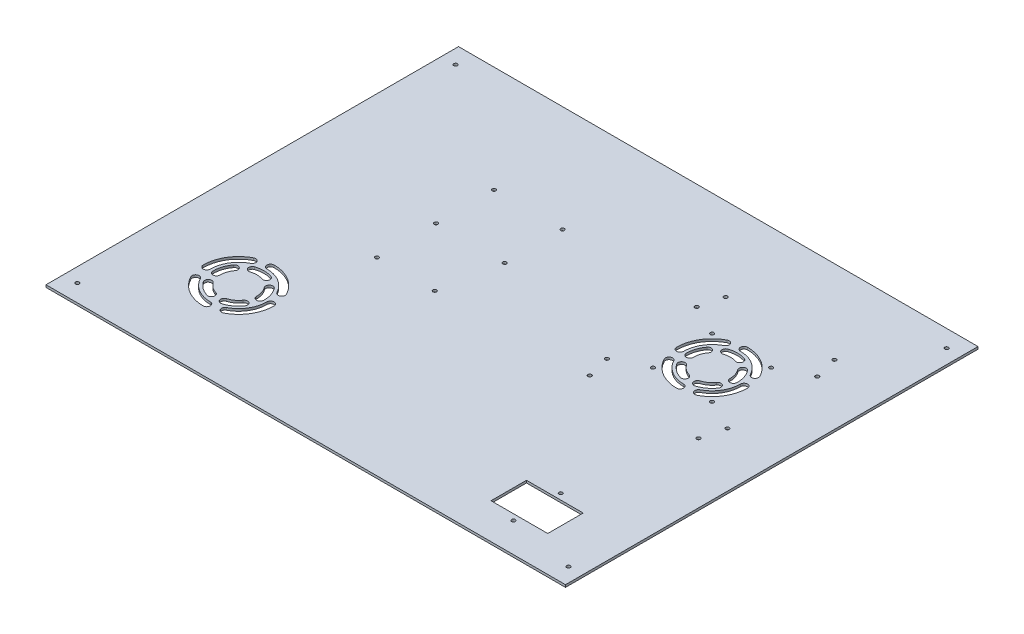
SolidWorks part; units mm, degrees
ref_plane "Alzado" through (0, 0, 0) normal (0, 0, 1) x (1, 0, 0)
ref_plane "Planta" through (0, 0, 0) normal (0, 1, 0) x (1, 0, 0)
ref_plane "Vista lateral" through (0, 0, 0) normal (1, 0, 0) x (0, 0, -1)
sketch "Croquis1" plane through (0, 0, 0) normal (0, 1, 0) x (1, 0, 0)
  line L1 (0, 0) -> (440.5, 0)
  line L2 (0, 0) -> (0, 320)
  line L3 (0, 320) -> (440.5, 320)
  line L4 (440.5, 0) -> (440.5, 320)
  dimension "D1" = 320
  dimension "D2" = 440.5
extrude "Saliente-Extruir1" add sketch "Croquis1" along normal blind 2
sketch "Croquis2" plane through (0, 2, 0) normal (0, 1, 0) x (1, 0, 0)
  line L0 (440.5, 320) -> (0, 320) construction
  line L1 (0, 320) -> (0, 0) construction
  line L2 (220.25, 320) -> (220.25, 0) construction
  line L3 (0, 0) -> (440.5, 0) construction
  line L4 (0, 160) -> (440.5, 160) construction
  line L5 (440.5, 0) -> (440.5, 320) construction
  circle A0 centre (12.5, 305) radius 1.55
  circle A1 centre (428, 305) radius 1.55
  circle A2 centre (428, 15) radius 1.55
  circle A3 centre (12.5, 15) radius 1.55
  dimension "D1" = 3.1
  dimension "D2" = 15
  dimension "D3" = 12.5
extrude "Cortar-Extruir1" cut sketch "Croquis2" against normal up to surface (2 mm away) up to face at (220.25, 0, -160)
sketch "Croquis3" plane through (0, 2, 0) normal (0, 1, 0) x (1, 0, 0)
  line L0 (440, 319.5) -> (0.5, 319.5)
  line L1 (0.5, 319.5) -> (0.5, 0.5)
  line L2 (0.5, 0.5) -> (440, 0.5)
  line L3 (440, 0.5) -> (440, 319.5)
  line L4 (0, 320) -> (0, 0)
  line L5 (0, 0) -> (440.5, 0)
  line L6 (440.5, 0) -> (440.5, 320)
  line L7 (440.5, 320) -> (0, 320)
  line L8 (0, 320) -> (0, 0)
  line L9 (0, 0) -> (440.5, 0)
  line L10 (440.5, 0) -> (440.5, 320)
  line L11 (440.5, 320) -> (0, 320)
  dimension "D1" = 0
  dimension "D2" = 0.5
extrude "Cortar-Extruir2" cut sketch "Croquis3" against normal up to surface (2 mm away) up to face at (12.5, 0, -16.55)
sketch "Croquis4" plane through (0, 2, 0) normal (0, 1, 0) x (1, 0, 0)
  line L0 (0.5, 0.5) -> (440, 0.5) construction
  line L1 (0.5, 319.5) -> (0.5, 0.5) construction
  line L2 (440, 0.5) -> (440, 319.5) construction
  line L4 (440, 319.5) -> (0.5, 319.5) construction
  line L13 (394, 259.5) -> (292, 259.5) construction
  line L14 (394, 259.5) -> (394, 183.5) construction
  line L15 (394, 183.5) -> (292, 183.5) construction
  line L16 (292, 259.5) -> (292, 183.5) construction
  line L17 (343, 259.5) -> (343, 183.5) construction
  line L18 (368, 196.5) -> (318, 196.5) construction
  line L19 (389, 164) -> (297, 164) construction
  line L20 (389, 164) -> (389, 279) construction
  line L21 (389, 279) -> (297, 279) construction
  line L22 (297, 164) -> (297, 279) construction
  line L23 (389, 164) -> (297, 279) construction
  line L24 (389, 279) -> (297, 164) construction
  line L25 (368, 196.5) -> (368, 246.5) construction
  line L26 (368, 246.5) -> (318, 246.5) construction
  line L27 (318, 196.5) -> (318, 246.5) construction
  line L28 (368, 196.5) -> (318, 246.5) construction
  line L29 (368, 246.5) -> (318, 196.5) construction
  circle A0 centre (82.5, 81.5) radius 27 construction
  arc A1 (82.5, 108.5) -> (106.4419, 93.9815) centre (82.5, 81.5) cw construction
  arc A2 (109.1021, 95.3683) -> (82.5, 111.5) centre (82.5, 81.5) ccw
  arc A3 (103.7817, 92.5947) -> (82.5, 105.5) centre (82.5, 81.5) ccw
  arc A4 (103.7817, 92.5947) -> (109.1021, 95.3683) centre (106.4419, 93.9815) ccw
  arc A5 (82.5, 111.5) -> (82.5, 105.5) centre (82.5, 108.5) ccw
  arc A6 (93.5947, 60.2183) -> (106.5, 81.5) centre (82.5, 81.5) ccw
  arc A7 (93.5947, 60.2183) -> (96.3683, 54.8979) centre (94.9815, 57.5581) ccw
  arc A8 (112.5, 81.5) -> (106.5, 81.5) centre (109.5, 81.5) ccw
  arc A9 (96.3683, 54.8979) -> (112.5, 81.5) centre (82.5, 81.5) ccw
  arc A10 (109.5, 81.5) -> (94.9815, 57.5581) centre (82.5, 81.5) cw construction
  arc A11 (61.2183, 70.4053) -> (82.5, 57.5) centre (82.5, 81.5) ccw
  arc A12 (61.2183, 70.4053) -> (55.8979, 67.6317) centre (58.5581, 69.0185) ccw
  arc A13 (82.5, 51.5) -> (82.5, 57.5) centre (82.5, 54.5) ccw
  arc A14 (55.8979, 67.6317) -> (82.5, 51.5) centre (82.5, 81.5) ccw
  arc A15 (82.5, 54.5) -> (58.5581, 69.0185) centre (82.5, 81.5) cw construction
  arc A16 (71.4053, 102.7817) -> (58.5, 81.5) centre (82.5, 81.5) ccw
  arc A17 (71.4053, 102.7817) -> (68.6317, 108.1021) centre (70.0185, 105.4419) ccw
  arc A18 (52.5, 81.5) -> (58.5, 81.5) centre (55.5, 81.5) ccw
  arc A19 (68.6317, 108.1021) -> (52.5, 81.5) centre (82.5, 81.5) ccw
  arc A20 (55.5, 81.5) -> (70.0185, 105.4419) centre (82.5, 81.5) cw construction
  circle A21 centre (82.5, 81.5) radius 18.5 construction
  arc A22 (76.5, 99) -> (88.5, 99) centre (82.5, 81.5) cw construction
  arc A23 (89.473, 101.8378) -> (75.527, 101.8378) centre (82.5, 81.5) ccw
  arc A24 (87.527, 96.1622) -> (77.473, 96.1622) centre (82.5, 81.5) ccw
  arc A25 (87.527, 96.1622) -> (89.473, 101.8378) centre (88.5, 99) ccw
  arc A26 (75.527, 101.8378) -> (77.473, 96.1622) centre (76.5, 99) ccw
  arc A27 (97.2894, 92.6141) -> (100.9976, 81.2015) centre (82.5, 81.5) cw construction
  arc A28 (103.9972, 81.153) -> (99.6877, 94.4164) centre (82.5, 81.5) ccw
  arc A29 (97.998, 81.2499) -> (94.8911, 90.8118) centre (82.5, 81.5) ccw
  arc A30 (97.998, 81.2499) -> (103.9972, 81.153) centre (100.9976, 81.2015) ccw
  arc A31 (99.6877, 94.4164) -> (94.8911, 90.8118) centre (97.2894, 92.6141) ccw
  arc A32 (97.6403, 70.8689) -> (87.9321, 63.8155) centre (82.5, 81.5) cw construction
  arc A33 (88.813, 60.9477) -> (100.0955, 69.145) centre (82.5, 81.5) ccw
  arc A34 (87.0513, 66.6832) -> (95.1852, 72.5929) centre (82.5, 81.5) ccw
  arc A35 (87.0513, 66.6832) -> (88.813, 60.9477) centre (87.9321, 63.8155) ccw
  arc A36 (100.0955, 69.145) -> (95.1852, 72.5929) centre (97.6403, 70.8689) ccw
  arc A37 (77.0679, 63.8155) -> (67.3597, 70.8689) centre (82.5, 81.5) cw construction
  arc A38 (64.9045, 69.145) -> (76.187, 60.9477) centre (82.5, 81.5) ccw
  arc A39 (69.8148, 72.5929) -> (77.9487, 66.6832) centre (82.5, 81.5) ccw
  arc A40 (69.8148, 72.5929) -> (64.9045, 69.145) centre (67.3597, 70.8689) ccw
  arc A41 (76.187, 60.9477) -> (77.9487, 66.6832) centre (77.0679, 63.8155) ccw
  arc A42 (64.0024, 81.2015) -> (67.7106, 92.6141) centre (82.5, 81.5) cw construction
  arc A43 (65.3123, 94.4164) -> (61.0028, 81.153) centre (82.5, 81.5) ccw
  arc A44 (70.1089, 90.8118) -> (67.002, 81.2499) centre (82.5, 81.5) ccw
  arc A45 (70.1089, 90.8118) -> (65.3123, 94.4164) centre (67.7106, 92.6141) ccw
  arc A46 (61.0028, 81.153) -> (67.002, 81.2499) centre (64.0024, 81.2015) ccw
  circle A47 centre (368, 246.5) radius 1.55
  circle A48 centre (368, 196.5) radius 1.55
  circle A57 centre (318, 196.5) radius 1.55
  circle A68 centre (318, 246.5) radius 1.55
  circle A69 centre (343, 221.5) radius 27 construction
  arc A84 (343, 248.5) -> (366.9419, 233.9815) centre (343, 221.5) cw construction
  circle A94 centre (428, 305) radius 1.55 construction
  arc A98 (369.6021, 235.3683) -> (343, 251.5) centre (343, 221.5) ccw
  arc A103 (364.2817, 232.5947) -> (343, 245.5) centre (343, 221.5) ccw
  arc A124 (364.2817, 232.5947) -> (369.6021, 235.3683) centre (366.9419, 233.9815) ccw
  arc A129 (343, 251.5) -> (343, 245.5) centre (343, 248.5) ccw
  circle A143 centre (394, 259.5) radius 1.55
  circle A144 centre (292, 259.5) radius 1.55
  circle A145 centre (292, 183.5) radius 1.55
  circle A146 centre (394, 183.5) radius 1.55
  circle A147 centre (389, 279) radius 1.55
  circle A148 centre (297, 279) radius 1.55
  circle A149 centre (297, 164) radius 1.55
  circle A150 centre (389, 164) radius 1.55
  arc A154 (370, 221.5) -> (355.4815, 197.5581) centre (343, 221.5) cw construction
  arc A159 (356.8683, 194.8979) -> (373, 221.5) centre (343, 221.5) ccw
  arc A164 (354.0947, 200.2183) -> (367, 221.5) centre (343, 221.5) ccw
  circle A165 centre (343, 221.5) radius 18.5 construction
  arc A166 (337, 239) -> (349, 239) centre (343, 221.5) cw construction
  arc A167 (349.973, 241.8378) -> (336.027, 241.8378) centre (343, 221.5) ccw
  arc A168 (348.027, 236.1622) -> (337.973, 236.1622) centre (343, 221.5) ccw
  arc A169 (348.027, 236.1622) -> (349.973, 241.8378) centre (349, 239) ccw
  arc A170 (336.027, 241.8378) -> (337.973, 236.1622) centre (337, 239) ccw
  arc A171 (354.0947, 200.2183) -> (356.8683, 194.8979) centre (355.4815, 197.5581) ccw
  arc A172 (373, 221.5) -> (367, 221.5) centre (370, 221.5) ccw
  arc A173 (343, 194.5) -> (319.0581, 209.0185) centre (343, 221.5) cw construction
  arc A174 (316.3979, 207.6317) -> (343, 191.5) centre (343, 221.5) ccw
  arc A175 (321.7183, 210.4053) -> (343, 197.5) centre (343, 221.5) ccw
  arc A176 (321.7183, 210.4053) -> (316.3979, 207.6317) centre (319.0581, 209.0185) ccw
  arc A177 (343, 191.5) -> (343, 197.5) centre (343, 194.5) ccw
  arc A178 (316, 221.5) -> (330.5185, 245.4419) centre (343, 221.5) cw construction
  arc A179 (329.1317, 248.1021) -> (313, 221.5) centre (343, 221.5) ccw
  arc A180 (331.9053, 242.7817) -> (319, 221.5) centre (343, 221.5) ccw
  arc A181 (331.9053, 242.7817) -> (329.1317, 248.1021) centre (330.5185, 245.4419) ccw
  arc A182 (313, 221.5) -> (319, 221.5) centre (316, 221.5) ccw
  circle A183 centre (343, 221.5) radius 18.5 construction
  arc A184 (357.7894, 232.6141) -> (361.4976, 221.2015) centre (343, 221.5) cw construction
  arc A185 (364.4972, 221.153) -> (360.1877, 234.4164) centre (343, 221.5) ccw
  arc A186 (358.498, 221.2499) -> (355.3911, 230.8118) centre (343, 221.5) ccw
  arc A187 (358.498, 221.2499) -> (364.4972, 221.153) centre (361.4976, 221.2015) ccw
  arc A188 (360.1877, 234.4164) -> (355.3911, 230.8118) centre (357.7894, 232.6141) ccw
  circle A189 centre (343, 221.5) radius 18.5 construction
  arc A190 (358.1403, 210.8689) -> (348.4321, 203.8155) centre (343, 221.5) cw construction
  arc A191 (349.313, 200.9477) -> (360.5955, 209.145) centre (343, 221.5) ccw
  arc A192 (347.5513, 206.6832) -> (355.6852, 212.5929) centre (343, 221.5) ccw
  arc A193 (347.5513, 206.6832) -> (349.313, 200.9477) centre (348.4321, 203.8155) ccw
  arc A194 (360.5955, 209.145) -> (355.6852, 212.5929) centre (358.1403, 210.8689) ccw
  circle A195 centre (343, 221.5) radius 18.5 construction
  arc A196 (337.5679, 203.8155) -> (327.8597, 210.8689) centre (343, 221.5) cw construction
  arc A197 (325.4045, 209.145) -> (336.687, 200.9477) centre (343, 221.5) ccw
  arc A198 (330.3148, 212.5929) -> (338.4487, 206.6832) centre (343, 221.5) ccw
  arc A199 (330.3148, 212.5929) -> (325.4045, 209.145) centre (327.8597, 210.8689) ccw
  arc A200 (336.687, 200.9477) -> (338.4487, 206.6832) centre (337.5679, 203.8155) ccw
  circle A201 centre (343, 221.5) radius 18.5 construction
  arc A202 (324.5024, 221.2015) -> (328.2106, 232.6141) centre (343, 221.5) cw construction
  arc A203 (325.8123, 234.4164) -> (321.5028, 221.153) centre (343, 221.5) ccw
  arc A204 (330.6089, 230.8118) -> (327.502, 221.2499) centre (343, 221.5) ccw
  arc A205 (330.6089, 230.8118) -> (325.8123, 234.4164) centre (328.2106, 232.6141) ccw
  arc A206 (321.5028, 221.153) -> (327.502, 221.2499) centre (324.5024, 221.2015) ccw
  point P9 (96.5, 104.5868)
  point P19 (105.5868, 67.5)
  point P26 (68.5, 58.4132)
  point P33 (59.4132, 95.5)
  point P38 (82.5, 81.5)
  point P40 (82.5, 100)
  point P48 (100.0945, 87.2168)
  point P51 (343, 221.5)
  point P57 (93.374, 66.5332)
  point P64 (71.626, 66.5332)
  point P71 (64.9055, 87.2168)
  point P76 (82.5, 81.5)
  point P83 (0, 0)
  point P88 (357, 244.5868)
  point P100 (366.0868, 207.5)
  point P107 (329, 198.4132)
  point P114 (319.9132, 235.5)
  point P119 (343, 240)
  point P125 (302, 221.5)
  point P129 (360.5945, 227.2168)
  point P137 (353.874, 206.5332)
  point P147 (332.126, 206.5332)
  point P157 (325.4055, 227.2168)
  point P171 (343, 221.5)
  point P183 (302, 221.5)
  dimension "D1" = 54
  dimension "D7" = 37
  dimension "D13" = 54
  dimension "D18" = 6
  dimension "D28" = 3.1
  dimension "D16" = 37
  dimension "D2" = 81
  dimension "D3" = 82
  dimension "D4" = 28
  dimension "D5" = 6
  dimension "D8" = 12
  dimension "D9" = 6
  dimension "D11" = 50
  dimension "D12" = 50
  dimension "D14" = 28
  dimension "D15" = 6
  dimension "D17" = 12
  dimension "D26" = 102
  dimension "D27" = 76
  dimension "D29" = 46
  dimension "D30" = 60
  dimension "D31" = 92
  dimension "D32" = 115
  dimension "D6" = 4
  dimension "D10" = 5
extrude "Cortar-Extruir3" cut sketch "Croquis4" against normal up to surface (2 mm away) up to face at (12.5, 0, -306.55)
sketch "Croquis5" plane through (0, 0, 0) normal (0, -1, 0) x (1, 0, 0)
  line L0 (395, -45.5) -> (347, -45.5) construction
  line L1 (395, -60.5) -> (347, -60.5)
  line L2 (395, -60.5) -> (395, -30.5)
  line L3 (395, -30.5) -> (347, -30.5)
  line L4 (347, -60.5) -> (347, -30.5)
  line L5 (440, -0.5) -> (440, -319.5) construction
  line L6 (0.5, -0.5) -> (440, -0.5) construction
  circle A1 centre (371, -25.5) radius 1.55
  circle A2 centre (371, -65.5) radius 1.55
  dimension "D3" = 3.1
  dimension "D1" = 48
  dimension "D2" = 30
  dimension "D4" = 5
  dimension "D5" = 24
  dimension "D6" = 45
  dimension "D7" = 30
extrude "Cortar-Extruir4" cut sketch "Croquis5" against normal up to surface (2 mm away) up to face at (318, 2, -244.95)
sketch "Croquis6" plane through (0, 0, 0) normal (0, -1, 0) x (1, 0, 0)
  line L1 (178.5, -259.5) -> (120.5, -259.5) construction
  line L2 (178.5, -259.5) -> (178.5, -210.5) construction
  line L3 (178.5, -210.5) -> (120.5, -210.5) construction
  line L4 (120.5, -259.5) -> (120.5, -210.5) construction
  line L5 (0.5, -319.5) -> (0.5, -0.5) construction
  line L6 (440, -319.5) -> (0.5, -319.5) construction
  circle A0 centre (178.5, -259.5) radius 1.55
  circle A1 centre (178.5, -210.5) radius 1.55
  circle A2 centre (120.5, -210.5) radius 1.55
  circle A3 centre (120.5, -259.5) radius 1.55
  dimension "D3" = 3.1
  dimension "D1" = 49
  dimension "D2" = 58
  dimension "D4" = 60
  dimension "D5" = 120
extrude "Cortar-Extruir5" cut sketch "Croquis6" against normal up to surface (2 mm away) up to face at (371, 2, -67.05)
sketch "Croquis7" plane through (0, 0, 0) normal (0, -1, 0) x (1, 0, 0)
  line L0 (0.5, -319.5) -> (0.5, -0.5) construction
  line L1 (0.5, -0.5) -> (440, -0.5) construction
  circle A0 centre (169.4, -160.5) radius 1.55
  circle A1 centre (120.5, -160.5) radius 1.55
  dimension "D1" = 3.1
  dimension "D2" = 48.9
  dimension "D3" = 120
  dimension "D4" = 160
extrude "Cortar-Extruir6" cut sketch "Croquis7" against normal up to surface (2 mm away) up to face at (120.5, 2, -261.05)
sketch "Croquis8" plane through (0, 0, 0) normal (0, -1, 0) x (1, 0, 0)
  line L1 (440, -319.5) -> (0.5, -319.5)
  line L2 (440, -319.5) -> (440, -349.5)
  line L3 (440, -349.5) -> (0.5, -349.5)
  line L4 (0.5, -319.5) -> (0.5, -349.5)
  dimension "D1" = 30
extrude "Saliente-Extruir2" add sketch "Croquis8" against normal up to surface (2 mm away) up to face at (169.4, 2, -162.05)
sketch "Croquis9" plane through (0, 0, 0) normal (0, -1, 0) x (1, 0, 0)
  line L0 (0.5, -349.5) -> (440, -349.5) construction
  line L1 (0.5, -349.5) -> (0.5, -0.5) construction
  line L2 (440, -0.5) -> (440, -349.5) construction
  circle A0 centre (428, -335) radius 1.55
  circle A1 centre (12.5, -335) radius 1.55
  circle A2 centre (428, -305) radius 1.55 construction
  dimension "D1" = 14.5
  dimension "D2" = 14.5
  dimension "D3" = 12
  dimension "D4" = 12
extrude "Cortar-Extruir7" cut sketch "Croquis9" against normal up to surface (2 mm away) up to face at (169.4, 2, -162.05)
sketch "Croquis10" plane through (0, 0, 0) normal (0, -1, 0) x (1, 0, 0)
  circle A0 centre (428, -305) radius 1.75
  circle A1 centre (12.5, -305) radius 1.75
  dimension "D1" = 3.5
  dimension "D2" = 3.5
extrude "Saliente-Extruir3" add sketch "Croquis10" against normal up to surface (2 mm away) up to face at (428, 2, -336.55)
